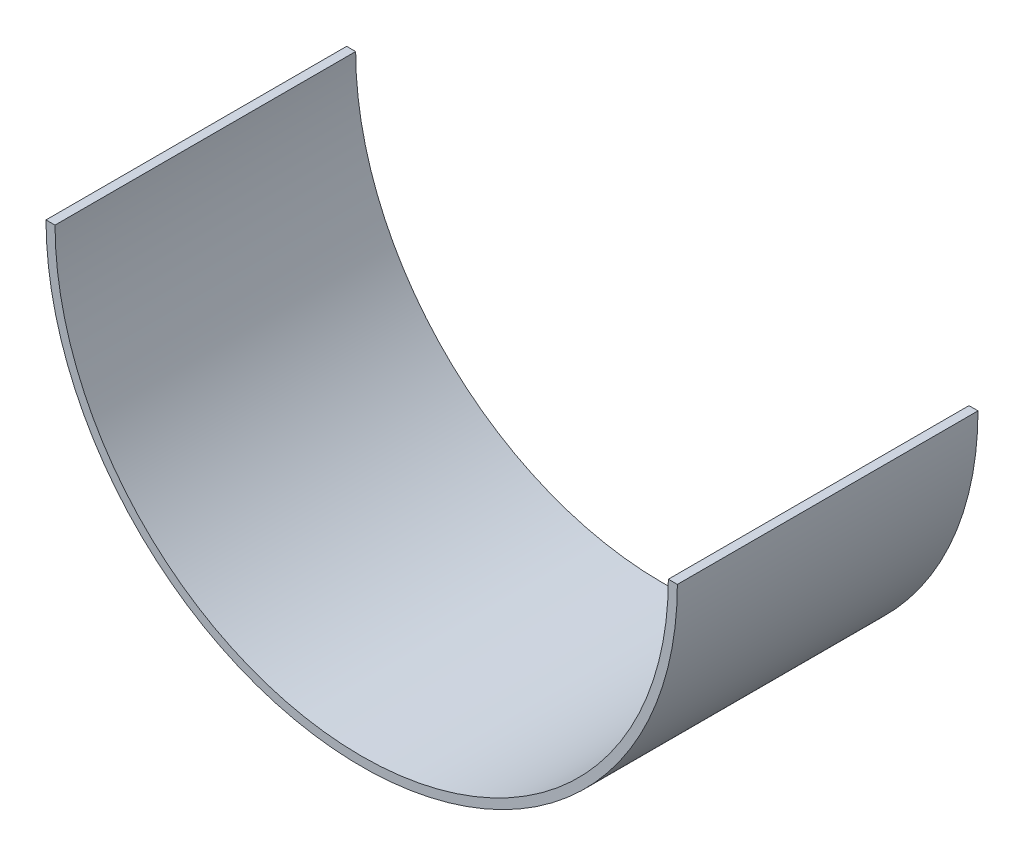
SolidWorks part; units mm, degrees
ref_plane "Plan de face" through (0, 0, 0) normal (0, 0, 1) x (1, 0, 0)
ref_plane "Plan de dessus" through (0, 0, 0) normal (0, 1, 0) x (1, 0, 0)
ref_plane "Plan de droite" through (0, 0, 0) normal (1, 0, 0) x (0, 0, -1)
sketch "Esquisse1" plane through (0, 0, 0) normal (0, 0, 1) x (1, 0, 0)
  circle A0 centre (0, 0) radius 52.5
  dimension "D1" = 105
extrude "Boss.-Extru.1" add sketch "Esquisse1" along normal blind 50
sketch "Esquisse2" plane through (0, 0, 50) normal (0, 0, 1) x (1, 0, 0)
  line L1 (-52.5, 0) -> (57.6068, 0)
  line L2 (-52.5, 0) -> (-52.5, 56.8107)
  line L3 (-52.5, 56.8107) -> (57.6068, 56.8107)
  line L4 (57.6068, 0) -> (57.6068, 56.8107)
  circle A0 centre (0, 0) radius 51
  circle A1 centre (0, 0) radius 52.5 construction
  circle M2 centre (0, 0) radius 52.5
  dimension "D1" = 1.5
extrude "Enlèv. mat.-Extru.1" cut sketch "Esquisse2" against normal through all contours L1 A0 | L1 L4 L3 L2 M2 | L1 A0
sketch "Esquisse3" plane through (0, 0, 50) normal (0, 0, 1) x (1, 0, 0)
  line L0 (-52.5, 0) -> (52.5, 0)
  circle A0 centre (0, 0) radius 52.5 construction
  circle A1 centre (0, 0) radius 52.5
  circle M1 centre (0, 0) radius 51
  circle M2 centre (0, 0) radius 52.5
extrude "Enlèv. mat.-Extru.2" cut sketch "Esquisse3" against normal through all contours L0 M1 | L0 M2 M1
